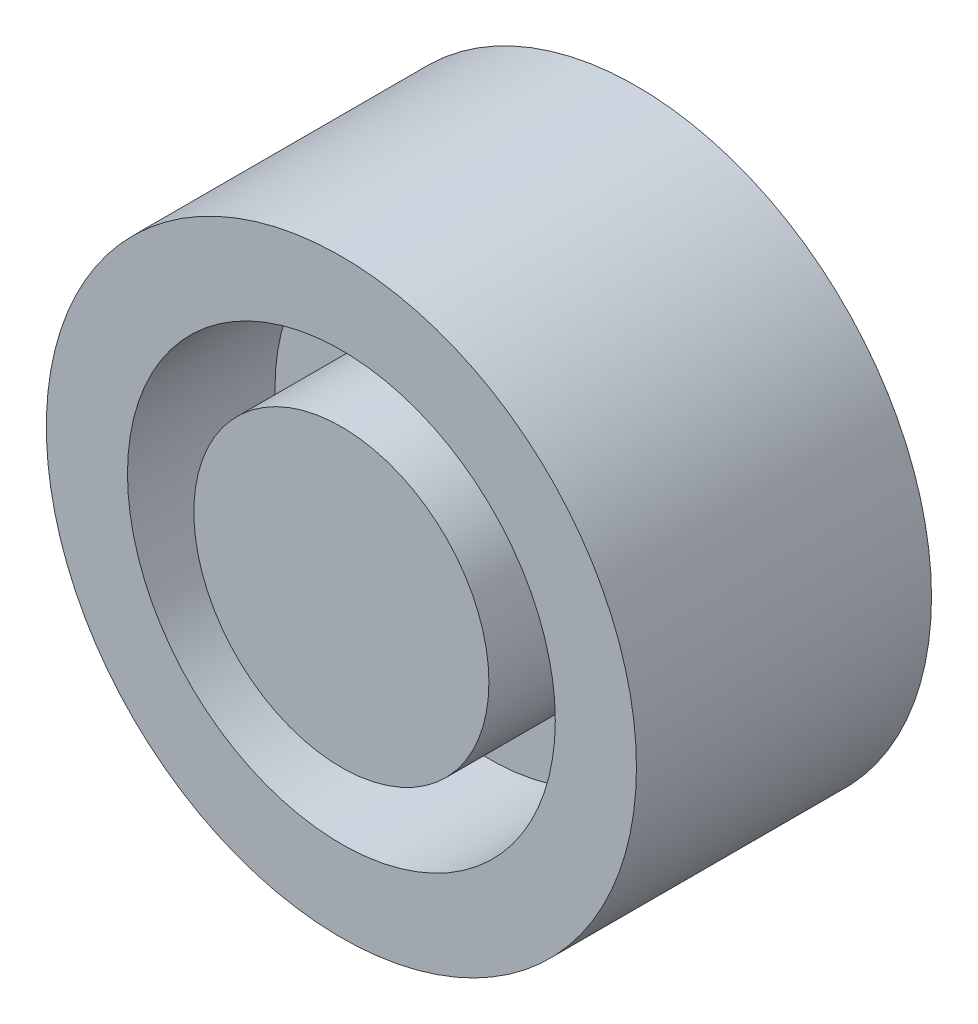
SolidWorks part; units mm, degrees
ref_plane "Front Plane" through (0, 0, 0) normal (0, 0, 1) x (1, 0, 0)
ref_plane "Top Plane" through (0, 0, 0) normal (0, 1, 0) x (1, 0, 0)
ref_plane "Right Plane" through (0, 0, 0) normal (1, 0, 0) x (0, 0, -1)
sketch "Sketch1" plane through (0, 0, 0) normal (0, 0, 1) x (1, 0, 0)
  circle A0 centre (0, 0) radius 2
extrude "Boss-Extrude1" add sketch "Sketch1" along normal blind 2
sketch "Sketch2" plane through (0, 0, 2) normal (0, 0, 1) x (1, 0, 0)
  circle A0 centre (0, 0) radius 1
  circle A1 centre (0, 0) radius 1.45
extrude "Cut-Extrude1" cut sketch "Sketch2" against normal blind 1
